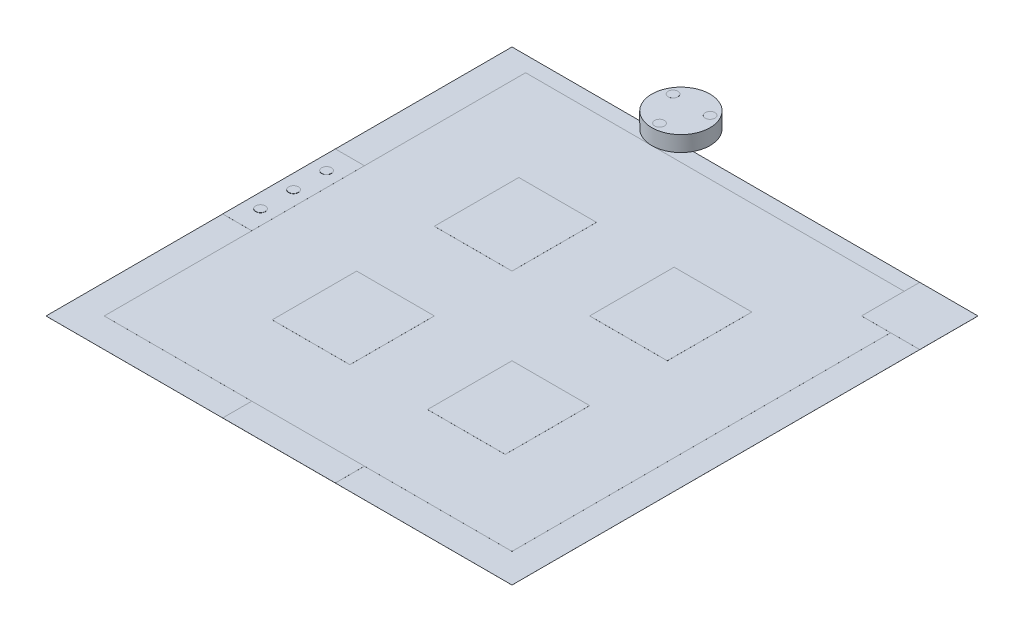
SolidWorks part; units mm, degrees
ref_plane "前视基准面" through (0, 0, 0) normal (0, 0, 1) x (1, 0, 0)
ref_plane "上视基准面" through (0, 0, 0) normal (0, 1, 0) x (1, 0, 0)
ref_plane "右视基准面" through (0, 0, 0) normal (1, 0, 0) x (0, 0, -1)
other "Configuration Table"
sketch "草图1" plane through (0, 0, 0) normal (0, 1, 0) x (1, 0, 0)
  line L1 (-1200, -1200) -> (1200, -1200)
  line L2 (-1200, -1200) -> (-1200, 1200)
  line L3 (-1200, 1200) -> (1200, 1200)
  line L4 (1200, -1200) -> (1200, 1200)
  line L5 (-1200, -1200) -> (1200, 1200) construction
  line L6 (-1200, 1200) -> (1200, -1200) construction
  point P0 (0, 0)
  dimension "D1" = 2400
  dimension "D2" = 2400
extrude "凸台-拉伸1" add sketch "草图1" along normal blind 0.1
sketch "草图3" plane through (0, 0.1, 0) normal (0, 1, 0) x (1, 0, 0)
  line L5 (-1050, 1120) -> (1050, 1120)
  line L6 (1050, 1120) -> (1050, -1050)
  line L9 (1050, -1050) -> (-1050, -1050)
  line L10 (-1050, -1050) -> (-1050, 1120)
  line L11 (1200, 1200) -> (-1200, 1200) construction
  line L12 (1200, -1200) -> (1200, 1200) construction
  line L13 (-1200, -1200) -> (1200, -1200) construction
  line L14 (-1200, 1200) -> (-1200, -1200) construction
  line L15 (200, 635) -> (200, -635)
  line L16 (-600, -635) -> (600, -635)
  line L17 (-600, -635) -> (-600, 635)
  line L18 (-600, 635) -> (600, 635)
  line L19 (600, -635) -> (600, 635)
  line L20 (-600, -635) -> (600, 635) construction
  line L21 (-600, 635) -> (600, -635) construction
  line L22 (-200, 635) -> (-200, -635)
  line L23 (-600, 200) -> (600, 200)
  line L24 (-600, -200) -> (600, -200)
  point P0 (0, 0)
  point P14 (0, 0)
  dimension "D1" = 80
  dimension "D2" = 150
  dimension "D3" = 150
  dimension "D4" = 150
  dimension "D5" = 1200
  dimension "D6" = 1270
  dimension "D7" = 400
  dimension "D8" = 400
  dimension "D9" = 200
  dimension "D10" = 200
extrude "凸台-拉伸5" add sketch "草图3" along normal blind 0.1 contours L10 L9 L6 L5 L19 L16 L17 L18 | L22 L23 L15 L18 | L24 L22 L16 L15 | L17 L24 L22 L23 | L15 L24 L19 L23 | L24 L17 L16 L22 | L22 L24 L15 L23 | L17 L23 L22 L18 | L15 L23 L19 L18 | L24 L15 L16 L19
sketch "草图4" plane through (0, 0.2, 0) normal (0, 1, 0) x (1, 0, 0)
  line L0 (1200, 1200) -> (900, 1200)
  line L1 (1200, 1200) -> (-1200, 1200) construction
  line L2 (900, 1200) -> (900, 900)
  line L3 (900, 900) -> (1200, 900)
  line L4 (1200, -1200) -> (1200, 1200) construction
  line L5 (1200, 900) -> (1200, 1200)
  dimension "D1" = 300
  dimension "D2" = 300
extrude "凸台-拉伸7" add sketch "草图4" along normal blind 0.1
sketch "草图5" plane through (0, 0.1, 0) normal (0, 1, 0) x (1, 0, 0)
  line L0 (0, 0) -> (0, -1956.9663) construction
  line L1 (290, -1200) -> (-290, -1200)
  line L2 (-1200, -1200) -> (1200, -1200) construction
  line L3 (-290, -1200) -> (-290, -1050)
  line L4 (1050, -1050) -> (-1050, -1050) construction
  line L5 (-290, -1050) -> (290, -1050)
  line L6 (290, -1200) -> (290, -1050)
  point P12 (0, -1050)
  point P13 (0, -1200)
  dimension "D1" = 290
extrude "凸台-拉伸9" add sketch "草图5" along normal blind 0.2
sketch "草图6" plane through (0, 0.1, 0) normal (0, 1, 0) x (1, 0, 0)
  line L0 (0, 0) -> (-1682.4519, 0) construction
  line L1 (-1200, -290) -> (-1200, 290)
  line L2 (-1200, 1200) -> (-1200, -1200) construction
  line L3 (-1200, 290) -> (-1050, 290)
  line L4 (-1050, -1050) -> (-1050, 1120) construction
  line L5 (-1050, 290) -> (-1050, -290)
  line L6 (-1050, -1050) -> (-1050, 1120) construction
  line L7 (-1200, -290) -> (-1050, -290)
  point P14 (-1050, 0)
  point P15 (-1200, 0)
  dimension "D1" = 290
extrude "凸台-拉伸10" add sketch "草图6" along normal blind 0.2
sketch "草图7" plane through (0, 0.2, 0) normal (0, 1, 0) x (1, 0, 0)
  line L0 (0, 0) -> (0, 1324.3587) construction
  line L1 (0, 0) -> (1529.3724, 0) construction
  line L2 (200, 200) -> (200, 635)
  line L3 (200, 635) -> (600, 635)
  line L4 (600, 635) -> (600, 200)
  line L5 (600, 200) -> (200, 200)
  line L6 (600, -200) -> (200, -200)
  line L7 (600, -635) -> (600, -200)
  line L8 (200, -635) -> (600, -635)
  line L9 (200, -200) -> (200, -635)
  line L10 (-200, -200) -> (-200, -635)
  line L11 (-200, -635) -> (-600, -635)
  line L12 (-600, -635) -> (-600, -200)
  line L13 (-600, -200) -> (-200, -200)
  line L14 (-600, 200) -> (-200, 200)
  line L15 (-600, 635) -> (-600, 200)
  line L16 (-200, 635) -> (-600, 635)
  line L17 (-200, 200) -> (-200, 635)
  dimension "D1" = 200
  dimension "D2" = 200
  dimension "D3" = 435
  dimension "D4" = 400
extrude "凸台-拉伸11" add sketch "草图7" along normal blind 0.2
sketch "草图10" plane through (0, 0, 0) normal (0, -1, 0) x (1, 0, 0)
  line L0 (0, 0) -> (0, -1600.6704) construction
  line L1 (0, 0) -> (1502.1449, 0) construction
  line L2 (1200, -1200) -> (-1200, -1200) construction
  circle A0 centre (-400, -1269.9) radius 150
  dimension "D1" = 300
  dimension "D2" = 400
  dimension "D3" = 69.9
extrude "凸台-拉伸14" add sketch "草图10" against normal blind 80
sketch "草图11" plane through (0, 80, 0) normal (0, 1, 0) x (1, 0, 0)
  line L0 (-400, 1269.9) -> (-400, 1107.4232) construction
  line L1 (-400, 1269.9) -> (-237.2791, 1363.8469) construction
  line L2 (-400, 1269.9) -> (-590.5256, 1379.9) construction
  circle A0 centre (-400, 1269.9) radius 110 construction
  circle A1 centre (-495.2628, 1324.9) radius 25
  circle A2 centre (-400, 1159.9) radius 25
  circle A3 centre (-304.7372, 1324.9) radius 25
  dimension "D1" = 220
  dimension "D4" = 50
  dimension "D5" = 50
  dimension "D6" = 50
  dimension "D2" = 120
  dimension "D3" = 120
extrude "凸台-拉伸15" add sketch "草图11" along normal blind 0.1
sketch "草图12" plane through (0, 0.3, 0) normal (0, 1, 0) x (1, 0, 0)
  line L0 (0, 0) -> (-1890.4291, 0) construction
  line L1 (-1050, -290) -> (-1050, 290) construction
  line L2 (-1050, -290) -> (-1050, 290) construction
  circle A0 centre (-1125, 0) radius 25
  circle A1 centre (-1125, 170) radius 25
  circle A2 centre (-1125, -170) radius 25
  dimension "D1" = 50
  dimension "D2" = 50
  dimension "D3" = 50
  dimension "D4" = 170
  dimension "D5" = 170
  dimension "D6" = 75
  dimension "D7" = 75
  dimension "D8" = 75
extrude "凸台-拉伸16" add sketch "草图12" along normal blind 1
